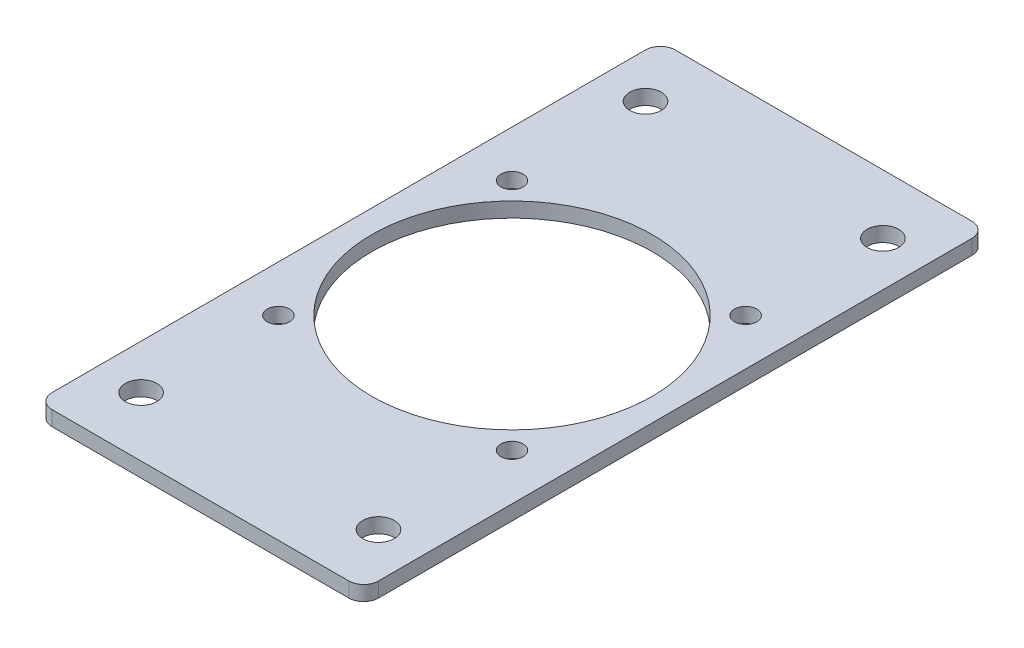
SolidWorks part; units mm, degrees
ref_plane "Front Plane" through (0, 0, 0) normal (0, 0, 1) x (1, 0, 0)
ref_plane "Top Plane" through (0, 0, 0) normal (0, 1, 0) x (1, 0, 0)
ref_plane "Right Plane" through (0, 0, 0) normal (1, 0, 0) x (0, 0, -1)
sketch "Sketch1" plane through (0, 0, 0) normal (0, 1, 0) x (1, 0, 0)
  line L1 (-34.925, -66.675) -> (34.925, -66.675)
  line L2 (-34.925, -66.675) -> (-34.925, 66.675)
  line L3 (-34.925, 66.675) -> (34.925, 66.675)
  line L4 (34.925, -66.675) -> (34.925, 66.675)
  line L5 (-34.925, -66.675) -> (34.925, 66.675) construction
  line L6 (-34.925, 66.675) -> (34.925, -66.675) construction
  point P0 (0, 0)
  dimension "D1" = 133.35
  dimension "D2" = 69.85
extrude "Boss-Extrude1" add sketch "Sketch1" along normal blind 3.175
sketch "Sketch2" plane through (0, 3.175, 0) normal (0, 1, 0) x (1, 0, 0)
  line L0 (-34.925, 66.675) -> (34.925, -66.675) construction
  circle A0 centre (0, 0) radius 30
  dimension "D1" = 60
extrude "Cut-Extrude1" cut sketch "Sketch2" against normal blind 3.175
hole_wizard "3/16 (0.1875) Diameter Hole1" positions "Sketch3" profile "Sketch4" hole size "3/16" standard "ANSI Inch" end condition up to next
sketch "Sketch3" plane through (0, 3.175, 0) normal (0, 1, 0) x (1, 0, 0)
  line L0 (-34.925, 66.675) -> (34.925, -66.675) construction
  line L3 (-25, -25) -> (25, -25) construction
  line L4 (-25, -25) -> (-25, 25) construction
  line L5 (-25, 25) -> (25, 25) construction
  line L6 (25, -25) -> (25, 25) construction
  line L7 (-25, -25) -> (25, 25) construction
  line L8 (-25, 25) -> (25, -25) construction
  point P7 (25, 25)
  point P10 (-25, -25)
  point P11 (-25, 25)
  point P12 (25, -25)
  dimension "D1" = 50
sketch "Sketch4" plane through (25, 3.175, 25) normal (1, 0, 0) x (0, 0, 1)
  line L0 (0, 0) -> (0, 3.175)
  line L1 (0, 3.175) -> (2.3812, 3.175)
  line L2 (2.3812, 3.175) -> (2.3812, 0)
  line L5 (2.3812, 0) -> (0, 0)
  line L11 (0, -6.35) -> (0, 107.95) construction
  dimension "Thru Hole Dia." = 4.7625
  dimension "Thru Hole Depth" = 3.175
hole_wizard "1/4 Clearance Hole1" positions "Sketch5" profile "Sketch6" hole size "1/4" standard "ANSI Inch" end condition up to next
sketch "Sketch5" plane through (0, 3.175, 0) normal (0, 1, 0) x (1, 0, 0)
  line L11 (-25.4, -53.975) -> (25.4, -53.975) construction
  line L12 (-25.4, -53.975) -> (-25.4, 53.975) construction
  line L13 (-25.4, 53.975) -> (25.4, 53.975) construction
  line L14 (25.4, -53.975) -> (25.4, 53.975) construction
  line L15 (-25.4, -53.975) -> (25.4, 53.975) construction
  line L16 (-25.4, 53.975) -> (25.4, -53.975) construction
  point P47 (0, 0)
  point P48 (25.4, 53.975)
  point P51 (-25.4, -53.975)
  point P52 (-25.4, 53.975)
  point P53 (25.4, -53.975)
  dimension "D1" = 50.8
  dimension "D2" = 107.95
sketch "Sketch6" plane through (0, 3.175, 0) normal (1, 0, 0) x (0, 0, 1)
  line L0 (0, 0) -> (0, 3.175)
  line L1 (0, 3.175) -> (3.3782, 3.175)
  line L2 (3.3782, 3.175) -> (3.3782, 0)
  line L5 (3.3782, 0) -> (0, 0)
  line L11 (0, -6.35) -> (0, 107.95) construction
  dimension "Thru Hole Dia." = 6.7564
  dimension "Thru Hole Depth" = 3.175
fillet "Fillet1" radius 3.175 4 edges at (34.925, 1.5875, 66.675) (-34.925, 1.5875, 66.675) (-34.925, 1.5875, -66.675) (34.925, 1.5875, -66.675)
